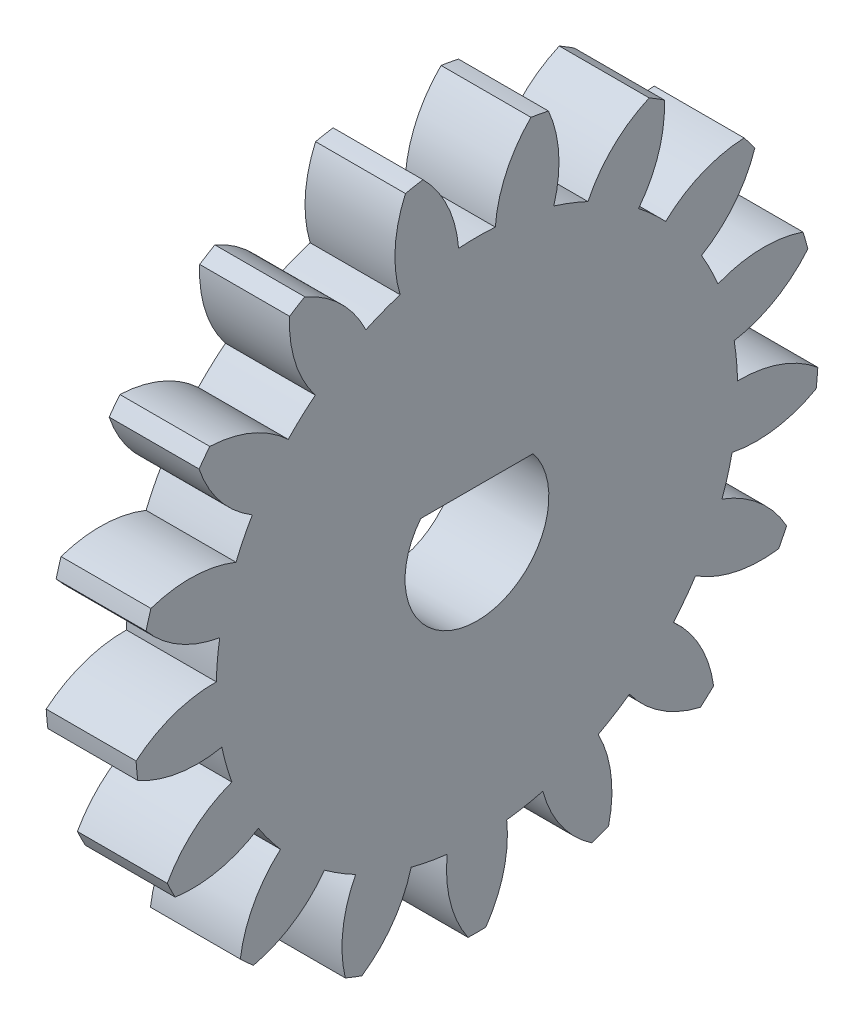
SolidWorks part; units mm, degrees
ref_plane "Plane1" through (0, 0, 0) normal (0, 0, 1) x (1, 0, 0)
ref_plane "Plane2" through (0, 0, 0) normal (0, 1, 0) x (1, 0, 0)
ref_plane "Plane3" through (0, 0, 0) normal (1, 0, 0) x (0, 0, -1)
sketch "HoldingSke" plane through (0, 0, 0) normal (0, 1, 0) x (1, 0, 0)
  line L0 (0, 0) -> (0.4782, -0.1462)
  line L1 (-15, 0) -> (100, 0) construction
  line L2 (0, 0) -> (-2.1039, 2.3779)
  line L3 (0, 0) -> (-11.863, 4.5341)
  line L4 (0, 0) -> (8.2586, 2.5249)
  line L5 (0, 0) -> (-46.8476, -17.4728)
  line L6 (0, 0) -> (-4.1448, -2.7965)
  line L7 (-2.1039, 2.3779) -> (8.6586, 51.2059)
  line L8 (-76.2, 54.61) -> (-74.8, 54.61)
  line L9 (-71.009, 38.7566) -> (-53.1078, 45.2721)
  line L10 (-76.2, 71.12) -> (104.1128, 71.12)
  line L11 (0, 0) -> (-5, 0)
  line L12 (-76.2, 101.6) -> (-76.133, 101.6)
  line L13 (24.9733, 27.94) -> (52.9518, 28.4284)
  line L14 (24.9733, 27.94) -> (24.9743, 27.94)
  line L15 (24.9733, 27.94) -> (100.4006, 29.5858)
  line L16 (-63.627, -2) -> (-12.827, -2)
  circle A0 centre (0, 0) radius 4
  circle A1 centre (0, 0) radius 14.499
  circle A2 centre (0, 0) radius 37.5
  circle A3 centre (0, 0) radius 4
  dimension "MHD" = 28.998
  dimension "Hub_dia" = 75
  dimension "Bore" = 8
  dimension "MBD" = 8
  dimension "Num_teeth" = 17
  dimension "Pitch" = 0.5
  dimension "Overall_len" = 50
  dimension "Show_teeth" = 17
  dimension "Thickness" = 5
  dimension "OAL" = 50.0001
  dimension "T_dim" = 1.4
  dimension "Ap" = 20
  dimension "H" = 19.05
  dimension "Pitch_radius" = 180.3128
  dimension "Width" = 5
  dimension "Backlash" = 0.067
  dimension "Addendum_fac" = 1
  dimension "Dedendum_fac" = 1.25
  dimension "Clearance_fac" = 0.25
  dimension "Dedendum_add" = 0.001
  dimension "Module" = 2
sketch "BasProSke" plane through (0, 0, 0) normal (0, 1, 0) x (1, 0, 0)
  line L0 (-10, 0) -> (60, 0) construction
  line L1 (0, 0) -> (0, 19)
  line L2 (0, 0) -> (5, 0)
  line L3 (5, 0) -> (5, 19)
  line L4 (5, 19) -> (0, 19)
  dimension "Thickness" = 5
  dimension "Diameter" = 38
revolve "Base-Revolve" add sketch "BasProSke" angle 360 about L0
sketch "TooCutSke" plane through (0, 0, 0) normal (1, 0, 0) x (0, 0, -1)
  line L1 (0, 0) -> (0, 107) construction
  line L2 (0, 0) -> (-1.6857, 16.9162) construction
  line L3 (0, 0) -> (-6.2247, 33.2991) construction
  line L4 (-1.6857, 16.9162) -> (-3.1123, 16.6495) construction
  arc A0 (1.0204, 14.4631) -> (-1.0204, 14.4631) centre (0, 0) ccw
  arc A1 (3.0261, 18.7832) -> (-3.0261, 18.7832) centre (0, 0) ccw
  circle A2 centre (0, 0) radius 17 construction
  circle A3 centre (0, 0) radius 15.9748 construction
  arc A4 (-1.0204, 14.4631) -> (-3.0261, 18.7832) centre (-7.8003, 13.9409) ccw
  arc A5 (3.0261, 18.7832) -> (1.0204, 14.4631) centre (7.8003, 13.9409) ccw
  dimension "Root_dia" = 28.998
  dimension "Overcut_dia" = 38.0508
  dimension "Pitch_dia" = 34
  dimension "Base_dia" = 31.9495
  dimension "Flank_rad" = 6.8
  dimension "Half_ang" = 10.588
  dimension "Half_CT" = 1.4513
extrude "ToothCut" cut sketch "TooCutSke" along normal through all
fillet "Breaks" [suppressed] radius 0.04
fillet "RootFillets" [suppressed] radius 0.501
pattern_circular "TeethCuts" count 17 over 360 about axis through (0, 0, 0) along (1, 0, 0) of "ToothCut", "RootFillets", "Breaks"
sketch "HubNeaOneSke" plane through (0, 0, 0) normal (-1, 0, 0) x (0, 0, 1)
  circle A0 centre (0, 0) radius 14.499
  dimension "Diameter" = 28.998
extrude "HubNearOne" [suppressed] add sketch "HubNeaOneSke" along normal blind 45.0001
sketch "HubNeaBotSke" plane through (0, 0, 0) normal (-1, 0, 0) x (0, 0, 1)
  circle A0 centre (0, 0) radius 14.499
  dimension "Diameter" = 28.998
extrude "HubNearBoth" [suppressed] add sketch "HubNeaBotSke" along normal blind 22.5
ref_plane "FarPln" through (5, 0, 0) normal (1, 0, 0) x (0, 0, -1)
sketch "HubFarSke" plane through (5, 0, 0) normal (1, 0, 0) x (0, 0, -1)
  circle A0 centre (0, 0) radius 14.499
  dimension "Diameter" = 28.998
extrude "HubFar" [suppressed] add sketch "HubFarSke" along normal blind 22.5
sketch "BorSke" plane through (0, 0, 0) normal (1, 0, 0) x (0, 0, -1)
  circle A0 centre (0, 0) radius 4
  dimension "Diameter" = 8
extrude "Bore" cut sketch "BorSke" along normal mid plane 100.0001
sketch "KeySke" plane through (0, 0, 0) normal (1, 0, 0) x (0, 0, -1)
  line L0 (-1.5, 0) -> (-1.5, 5.4)
  line L1 (-1.5, 5.4) -> (1.5, 5.4)
  line L2 (1.5, 5.4) -> (1.5, 0)
  line L3 (0, 0) -> (0, 34) construction
  line L4 (-1.5, 0) -> (1.5, 0)
  dimension "Offset" = 5.4
  dimension "Width" = 3
extrude "Keyway" [suppressed] cut sketch "KeySke" along normal mid plane 100.0001
pattern_circular "Keyway2" [suppressed] count 2 every 90 about axis through (-10, 0, 0) along (1, 0, 0)
sketch "Sketch1" plane through (5, 0, 0) normal (1, 0, 0) x (0, 0, -1)
  line L0 (-3.1225, 2.5) -> (3.1225, 2.5)
  circle A0 centre (0, 0) radius 4
  dimension "D2" = 8
  dimension "D1" = 2.5
extrude "Boss-Extrude1" add sketch "Sketch1" against normal blind 5 contours L0 A0
equation "' \"Module@HoldingSke\" = 6.35"
equation "' \"Num_teeth@HoldingSke\" = 12"
equation "' \"Ap@HoldingSke\" =  20"
equation "' \"Ap@HoldingSke\" = 20"
equation "' \"Width@HoldingSke\" = 0.5 * 25.4"
equation "' \"Hub_dia@HoldingSke\"= 1 * 25.4"
equation "' \"Hub_dia@HoldingSke\" = 1 * 25.4"
equation "' \"Overall_len@HoldingSke\" = 1.0 * 25.4"
equation "' \"Bore@HoldingSke\" = 0.75 * 25.4"
equation "' \"T_dim@HoldingSke\" = 0.1 * 25.4"
equation "' \"Width@KeySke\" = 0.25 * 25.4"
equation "' \"Show_teeth@HoldingSke\" = 13"
equation "' \"Backlash@HoldingSke\" = 0.009 * 25.4"
equation "' \"Addendum_fac@HoldingSke\" = 1.0"
equation "' \"Dedendum_fac@HoldingSke\" = 1.25"
equation "' \"Dedendum_add@HoldingSke\" = 0.00005 * 25.4"
equation "' \"Clearance_fac@HoldingSke\" = 0.25"
equation "\"Pitch@HoldingSke\" = 1 / \"Module@HoldingSke\""
equation "\"Overcut_dia@TooCutSke\" = (\"Num_teeth@HoldingSke\" + 2 * \"Addendum_fac@HoldingSke\") / \"Pitch@HoldingSke\" + 0.002 * 25.4"
equation "\"Pitch_dia@TooCutSke\" = \"Num_teeth@HoldingSke\" / \"Pitch@HoldingSke\""
equation "\"Base_dia@TooCutSke\" = \"Num_teeth@HoldingSke\" / \"Pitch@HoldingSke\" * cos((\"Ap@HoldingSke\"  * 3.14159265 / 180))"
equation "\"Root_dia@TooCutSke\" = (\"Num_teeth@HoldingSke\" + 2) / \"Pitch@HoldingSke\" - 2 * (\"Addendum_fac@HoldingSke\" + \"Dedendum_fac@HoldingSke\") / \"Pitch@HoldingSke\" - \"Dedendum_add@HoldingSke\" * 2"
equation "\"Half_ang@TooCutSke\" = 180 / \"Num_teeth@HoldingSke\""
equation "\"Half_CT@TooCutSke\" = \"Num_teeth@HoldingSke\" / \"Pitch@HoldingSke\" * sin((3.14159265 / 2 / \"Num_teeth@HoldingSke\")) / 2 - 7 * \"Backlash@HoldingSke\" / 4"
equation "\"Flank_rad@TooCutSke\" = \"Num_teeth@HoldingSke\" / \"Pitch@HoldingSke\" / 5"
equation "\"Radius@RootFillets\" = \"Clearance_fac@HoldingSke\" / \"Pitch@HoldingSke\" + \"Dedendum_add@HoldingSke\""
equation "\"Break_rad@Breaks\" = 0.02 / \"Pitch@HoldingSke\""
equation "\"Thickness@HoldingSke\" = \"Width@HoldingSke\""
equation "\"OAL@HoldingSke\" = \"Thickness@HoldingSke\""
equation "\"MHD@HoldingSke\" = (\"Num_teeth@HoldingSke\" + 2) / \"Pitch@HoldingSke\" - 2 * (\"Addendum_fac@HoldingSke\" + \"Dedendum_fac@HoldingSke\")  / \"Pitch@HoldingSke\" - \"Dedendum_add@HoldingSke\" * 2"
equation "\"MBD@HoldingSke\" = (\"Num_teeth@HoldingSke\" + 2) / \"Pitch@HoldingSke\" - 2 * (\"Addendum_fac@HoldingSke\" + \"Dedendum_fac@HoldingSke\")  / \"Pitch@HoldingSke\" - \"Dedendum_add@HoldingSke\" * 2 - 0.002 * 25.4"
equation "\"MHD@HoldingSke\" = ((sgn( \"MHD@HoldingSke\" - \"Hub_dia@HoldingSke\" )-1)*( \"MHD@HoldingSke\" - \"Hub_dia@HoldingSke\" ))/-2+ \"Hub_dia@HoldingSke\""
equation "\"MBD@HoldingSke\" = ((sgn( \"MBD@HoldingSke\" - \"Bore@HoldingSke\" )-1)*( \"MBD@HoldingSke\" - \"Bore@HoldingSke\" ))/-2+ \"Bore@HoldingSke\""
equation "\"OAL@HoldingSke\" = ((sgn( \"OAL@HoldingSke\" - \"Overall_len@HoldingSke\" )+1)*( \"OAL@HoldingSke\" - \"Overall_len@HoldingSke\" ))/2 + \"Overall_len@HoldingSke\" + 0.000002 * 25.4"
equation "\"Num_teeth@TeethCuts\" = int( \"Show_teeth@HoldingSke\" ) + 1"
equation "\"Num_teeth@TeethCuts\" = ((sgn( \"Num_teeth@TeethCuts\" - \"Num_teeth@HoldingSke\" )-1)*( \"Num_teeth@TeethCuts\" - \"Num_teeth@HoldingSke\" ))/-2+ \"Num_teeth@HoldingSke\""
equation "\"Num_teeth@TeethCuts\" = ((sgn( \"Num_teeth@TeethCuts\" - 2.0)+1)*( \"Num_teeth@TeethCuts\" - 2.0))/2 +2.0"
equation "\"Angle@TeethCuts\" = 360.0 / \"Num_teeth@HoldingSke\""
equation "\"Diameter@BasProSke\" = (\"Num_teeth@HoldingSke\" + 2 * \"Addendum_fac@HoldingSke\") / \"Pitch@HoldingSke\""
equation "\"Thickness@BasProSke\"  = \"Thickness@HoldingSke\""
equation "' \"Fillet_rad@BasProSke\" =  \"Thickness@HoldingSke\" * 0.05"
equation "' \"Fillet_rad@BasProSke\" = \"Thickness@HoldingSke\" * 0.05"
equation "\"MHD@HoldingSke\" = ((sgn( \"MHD@HoldingSke\" - \"Root_dia@TooCutSke\" )-1)*( \"MHD@HoldingSke\" - \"Root_dia@TooCutSke\" ))/-2+ \"Root_dia@TooCutSke\""
equation "\"Diameter@HubNeaOneSke\" = \"MHD@HoldingSke\""
equation "\"Length@HubNearOne\" = \"OAL@HoldingSke\" - \"Thickness@BasProSke\""
equation "\"Diameter@HubNeaBotSke\" = \"MHD@HoldingSke\""
equation "\"Length@HubNearBoth\" = ( \"OAL@HoldingSke\" - \"Thickness@BasProSke\" ) / 2.0"
equation "\"Thickness@FarPln\" = \"Thickness@BasProSke\""
equation "\"Diameter@HubFarSke\" = \"MHD@HoldingSke\""
equation "\"Length@HubFar\" = ( \"OAL@HoldingSke\" - \"Thickness@BasProSke\" ) / 2.0"
equation "\"Diameter@BorSke\" = \"MBD@HoldingSke\""
equation "\"D1@Bore\" = \"OAL@HoldingSke\" * 2.0"
equation "\"D1@Keyway\" = \"OAL@HoldingSke\" * 2.0"
equation "\"Offset@KeySke\" = \"T_dim@HoldingSke\" + \"MBD@HoldingSke\" / 2.0"
